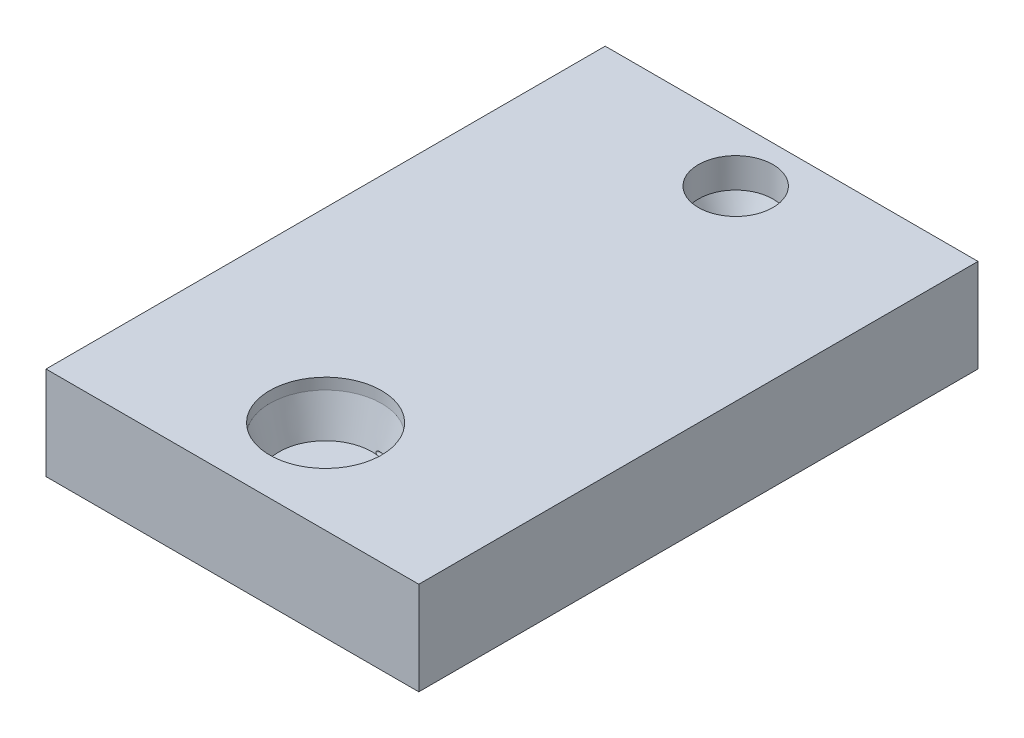
SolidWorks part; units mm, degrees
ref_plane "Front Plane" through (0, 0, 0) normal (0, 0, 1) x (1, 0, 0)
ref_plane "Top Plane" through (0, 0, 0) normal (0, 1, 0) x (1, 0, 0)
ref_plane "Right Plane" through (0, 0, 0) normal (1, 0, 0) x (0, 0, -1)
sketch "Sketch1" plane through (0, 0, 0) normal (0, 0, 1) x (1, 0, 0)
  line L1 (-20, 5) -> (20, 5)
  line L2 (-20, 5) -> (-20, -5)
  line L3 (-20, -5) -> (20, -5)
  line L4 (20, 5) -> (20, -5)
  line L5 (-20, 5) -> (20, -5) construction
  line L6 (-20, -5) -> (20, 5) construction
  point P0 (0, 0)
  dimension "D1" = 10
  dimension "D2" = 40
extrude "Boss-Extrude1" add sketch "Sketch1" along normal blind 60
ref_plane "Plane1" through (0, 0, 0) normal (0, 1, 0) x (1, 0, 0)
sketch "Sketch2" plane through (0, 0, 0) normal (0, 1, 0) x (1, 0, 0)
  line L1 (-20, -60) -> (20, -60) construction
  line L5 (0, -50) -> (0, -46)
  line L6 (1, -45) -> (15, -45)
  line L7 (15, -42) -> (0, -42)
  line L8 (0, -42) -> (-15, -42)
  line L9 (-15, -39) -> (15, -39)
  line L10 (15, -36) -> (-15, -36)
  line L11 (-15, -33) -> (15.3556, -33)
  line L12 (15.3556, -30) -> (-15, -30)
  line L13 (-15, -27) -> (15, -27)
  line L14 (15, -24) -> (-15, -24)
  line L15 (-15, -21) -> (15, -21)
  line L16 (15, -18) -> (-15, -18)
  line L17 (-15, -15) -> (15, -15)
  line L18 (15, -12) -> (1, -12)
  line L19 (0, -11) -> (0, -6)
  arc A0 (15, -45) -> (15, -42) centre (15, -43.5) ccw
  arc A1 (-15, -42) -> (-15, -39) centre (-15, -40.5) cw
  arc A2 (15, -39) -> (15, -36) centre (15, -37.5) ccw
  arc A3 (-15, -36) -> (-15, -33) centre (-15, -34.5) cw
  arc A4 (15.3556, -33) -> (15.3556, -30) centre (15.3556, -31.5) ccw
  arc A5 (-15, -30) -> (-15, -27) centre (-15, -28.5) cw
  arc A6 (15, -27) -> (15, -24) centre (15, -25.5) ccw
  arc A7 (-15, -24) -> (-15, -21) centre (-15, -22.5) cw
  arc A8 (15, -21) -> (15, -18) centre (15, -19.5) ccw
  arc A9 (-15, -18) -> (-15, -15) centre (-15, -16.5) cw
  arc A10 (15, -15) -> (15, -12) centre (15, -13.5) ccw
  arc A11 (0, -46) -> (1, -45) centre (1, -46) cw
  arc A12 (1, -12) -> (0, -11) centre (1, -11) cw
  point P5 (0, -45)
  point P9 (0, -12)
  dimension "D5" = 1
  dimension "D1" = 10
  dimension "D2" = 5
  dimension "D3" = 15
  dimension "D4" = 15
  dimension "D16" = 6
ref_plane "Plane2" through (0, 0, 6) normal (0, 0, -1) x (-1, 0, 0)
sketch "Sketch10" plane through (0, 0, 6) normal (0, 0, -1) x (-1, 0, 0)
  circle A0 centre (0, 0) radius 0.2
  dimension "D1" = 0.4
sketch "Sketch11" plane through (0, 0, 6) normal (0, 0, -1) x (-1, 0, 0)
sweep "Cut-Sweep1" cut profiles "Sketch10" path "Sketch2"
ref_plane "Plane4" through (0, 0, 0) normal (1, 0, 0) x (0, 0, -1)
sketch "Sketch13" plane through (0, 0, 0) normal (1, 0, 0) x (0, 0, -1)
  line L0 (-50, -0.2) -> (-55, -0.2)
  line L2 (-50, -0.2) -> (-50, 29.8)
  line L3 (-50, 29.8) -> (-56, 29.8)
  line L4 (-56, 29.8) -> (-56, 3.8)
  line L5 (-56, 3.8) -> (-55, -0.2)
  dimension "D1" = 5
  dimension "D3" = 6
  dimension "D4" = 30
revolve "Cut-Revolve1" cut sketch "Sketch13" angle 360 about L2
sketch "Sketch14" plane through (0, 0, 0) normal (1, 0, 0) x (0, 0, -1)
  line L0 (-6, -0.2) -> (-3, -0.2)
  line L2 (-6, -0.2) -> (-6, 29.8)
  line L3 (-6, 29.8) -> (-2, 29.8)
  line L4 (-2, 29.8) -> (-2, 1.8)
  line L5 (-2, 1.8) -> (-3, -0.2)
  dimension "D1" = 3
  dimension "D3" = 30
  dimension "D4" = 4
revolve "Cut-Revolve2" cut sketch "Sketch14" angle 360 about L2
